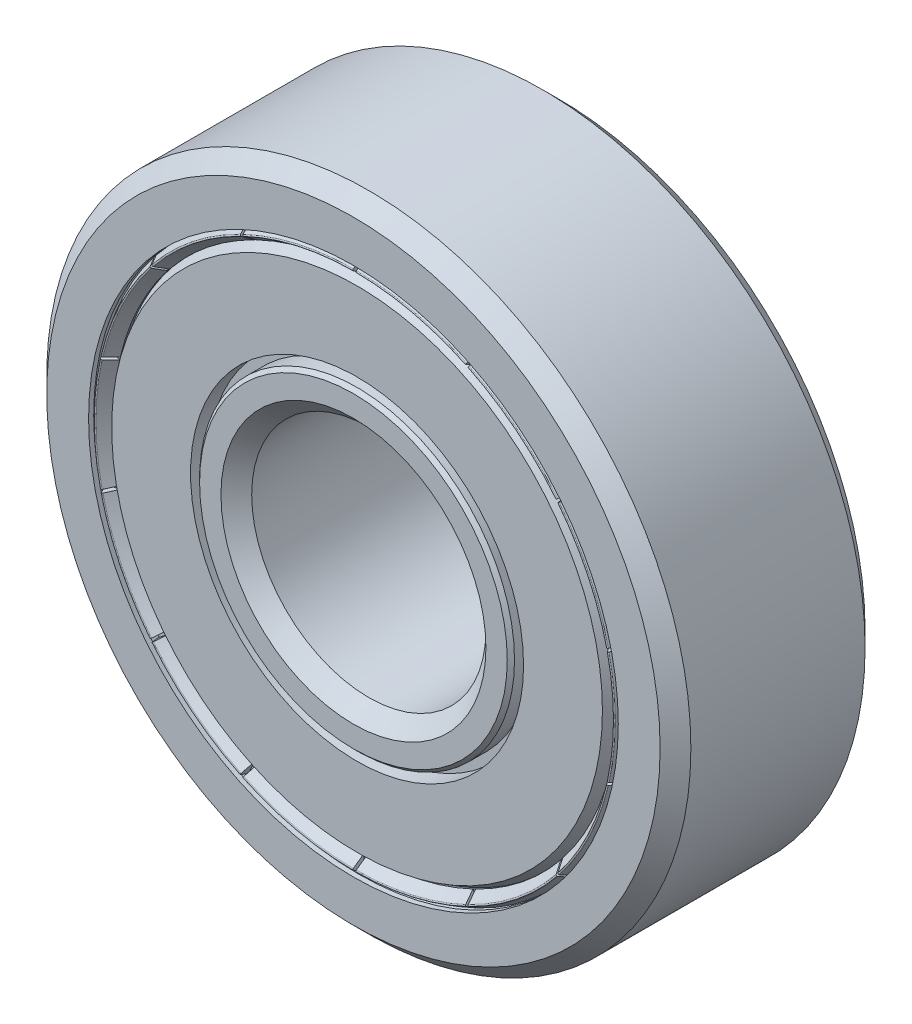
SolidWorks part; units mm, degrees
ref_plane "Front Plane" through (0, 0, 0) normal (0, 0, 1) x (1, 0, 0)
ref_plane "Top Plane" through (0, 0, 0) normal (0, 1, 0) x (1, 0, 0)
ref_plane "Right Plane" through (0, 0, 0) normal (1, 0, 0) x (0, 0, -1)
sketch "Sketch1" plane through (0, 0, 0) normal (0, 0, 1) x (1, 0, 0)
  circle A0 centre (0, 0) radius 4
  circle A1 centre (0, 0) radius 11
  dimension "OD" = 22
  dimension "ID" = 8
sketch "Sketch2" plane through (0, 0, 0) normal (1, 0, 0) x (0, 0, -1)
  line L0 (-3.5, 11) -> (3.5, 11)
  line L1 (-3.5, 4) -> (-3.5, -4) construction
  line L2 (3.5, 11) -> (3.5, -11) construction
  line L3 (-3.5, 0) -> (3.5, 0) construction
  line L6 (0, 11) -> (0, 4) construction
  circle A0 centre (0, 7.5) radius 2.45 construction
  point P8 (0, 11)
  dimension "Approx. Ball Dia." = 4.9
  dimension "Width" = 7
  dimension "For Shaft Diameter" = 8
  dimension "For Housing ID" = 22
sketch "Sketch3" plane through (0, 0, 0) normal (1, 0, 0) x (0, 0, -1)
  line L0 (0, 0) -> (0, 8) construction
  line L1 (-3.5, 4) -> (-3.5, -4) construction
  line L2 (2.975, 11) -> (-2.975, 11)
  line L3 (-2.975, 11) -> (-3.5, 10.475)
  line L4 (-3.5, 10.475) -> (-3.5, 9.046)
  line L5 (-3.5, 9.046) -> (-3.325, 9.046)
  line L6 (-3.325, 9.046) -> (-3.325, 9.498)
  line L7 (-3.325, 9.498) -> (-3.2013, 9.6218)
  line L8 (-3.2013, 9.6218) -> (-1.225, 9.6218)
  line L10 (-3.5, 11) -> (3.5, 11) construction
  line L12 (-3.325, 9.498) -> (-3.325, 9.95) construction
  line L13 (3.2013, 9.6218) -> (1.225, 9.6218)
  line L14 (3.325, 9.498) -> (3.2013, 9.6218)
  line L15 (3.325, 9.046) -> (3.325, 9.498)
  line L16 (3.5, 9.046) -> (3.325, 9.046)
  line L17 (3.5, 10.475) -> (3.5, 9.046)
  line L18 (2.975, 11) -> (3.5, 10.475)
  line L19 (2.975, 4) -> (-2.975, 4)
  line L20 (-2.975, 4) -> (-3.5, 4.525)
  line L21 (-3.5, 4.525) -> (-3.5, 5.2545)
  line L22 (-3.5, 5.2545) -> (-3.3763, 5.3782)
  line L23 (-3.3763, 5.3782) -> (-1.225, 5.3782)
  line L25 (3.3763, 5.3782) -> (1.225, 5.3782)
  line L26 (3.5, 5.2545) -> (3.3763, 5.3782)
  line L27 (3.5, 4.525) -> (3.5, 5.2545)
  line L28 (2.975, 4) -> (3.5, 4.525)
  circle A2 centre (0, 7.5) radius 2.45 construction
  arc A3 (-1.225, 9.6218) -> (1.225, 9.6218) centre (0, 7.5) cw
  arc A4 (-1.225, 5.3782) -> (1.225, 5.3782) centre (0, 7.5) ccw
  point P5 (0, 9.95)
  point P31 (0, 11)
  point P37 (0, 4)
  dimension "D1" = 45
  dimension "D2" = 0.175
  dimension "D3" = 2.45
  dimension "D4" = 0.525
revolve "Revolve1" add sketch "Sketch3" angle 360 about L3
sketch "Sketch4" plane through (0, 0, 0) normal (1, 0, 0) x (0, 0, -1)
  line L0 (0, 9.95) -> (0, 5.05)
  line L1 (0, 11) -> (0, 4) construction
  circle A0 centre (0, 7.5) radius 2.45 construction
  arc A1 (0, 5.05) -> (0, 9.95) centre (0, 7.5) cw
revolve "Revolve2" add sketch "Sketch4" angle 360 about L6
pattern_circular "CirPattern1" count 7 over 360 about axis through (0, 0, 0) along (0, 0, 1) of bodies 106
sketch "Sketch5" plane through (0, 0, 0) normal (1, 0, 0) x (0, 0, -1)
  line L0 (-2.45, 7.5) -> (-2.45, 5.3782) construction
  line L1 (-3.3763, 5.3782) -> (-1.225, 5.3782) construction
  line L3 (-2.45, 5.3782) -> (-2.7588, 5.3782)
  line L4 (-2.7588, 5.3782) -> (-2.7588, 5.687)
  line L5 (-2.7588, 5.687) -> (-3.3763, 5.687)
  line L6 (-3.3763, 5.687) -> (-3.3763, 8.3808)
  line L7 (-3.3763, 8.3808) -> (-2.7588, 8.7373)
  line L8 (-2.7588, 8.7373) -> (-2.45, 8.7373)
  line L9 (-2.45, 8.7373) -> (-2.45, 5.3782)
  line L10 (0, 7.5) -> (0, 11) construction
  line L11 (2.7588, 8.7373) -> (2.45, 8.7373)
  line L12 (3.3763, 8.3808) -> (2.7588, 8.7373)
  line L13 (3.3763, 5.687) -> (3.3763, 8.3808)
  line L14 (2.7588, 5.687) -> (3.3763, 5.687)
  line L15 (2.7588, 5.3782) -> (2.7588, 5.687)
  line L16 (2.45, 5.3782) -> (2.7588, 5.3782)
  line L17 (2.45, 8.7373) -> (2.45, 5.3782)
  line L18 (-3.3763, 8.3808) -> (-3.0675, 8.3808) construction
  line L19 (-3.0675, 8.3808) -> (-2.7588, 8.3808) construction
  line L20 (-2.7588, 8.3808) -> (-2.45, 8.3808) construction
  line L21 (-2.7588, 8.7373) -> (-2.7588, 9.046) construction
  circle A0 centre (0, 7.5) radius 2.45 construction
  dimension "D1" = 30
revolve "Revolve3" add sketch "Sketch5" angle 360 about L3
sketch "Sketch6" plane through (0, 0, 0) normal (1, 0, 0) x (0, 0, -1)
  line L0 (-2.9945, 9.046) -> (-3.1938, 9.046)
  line L1 (-3.1938, 9.046) -> (-3.5, 8.8692)
  line L2 (-3.5, 8.8692) -> (-3.0995, 8.5888)
  line L4 (-3.3763, 8.3808) -> (-2.7588, 8.7373) construction
  line L5 (-2.9945, 8.6012) -> (-2.9945, 9.046)
  line L6 (-3.5, 9.046) -> (-3.325, 9.046) construction
  line L7 (-3.0995, 8.5888) -> (-3.0645, 8.5888)
  line L8 (-3.0645, 8.5888) -> (-2.9945, 8.6012)
  line L9 (-3.5, 10.475) -> (-3.5, -10.475) construction
  line L11 (-3.0645, 8.5888) -> (-3.0295, 8.5888) construction
  line L12 (-3.0295, 8.5888) -> (-2.9945, 8.5888) construction
  point P27 (-3.0941, 9.046)
  dimension "D1" = 30
  dimension "D3" = 10
  dimension "D2" = 35
  dimension "D4" = 0.035
  dimension "D5" = 0.3062
revolve "Revolve4" add sketch "Sketch6" angle 360 about L3
fillet "Fillet1" radius 0.035 1 edges at (8.8692, 0, 3.5)
sketch "Sketch7" plane through (0, 0, 0) normal (0, 0, 1) x (1, 0, 0)
  line L0 (-0.05, 9.046) -> (-0.05, 9.146)
  line L1 (-0.05, 9.046) -> (0.05, 9.046) construction
  line L2 (-0.05, 9.046) -> (-0.05, 8.5888)
  line L3 (-0.05, 8.5888) -> (0.05, 8.5888) construction
  line L4 (0.05, 9.046) -> (0.05, 8.5888)
  line L5 (-0.05, 9.146) -> (0.05, 9.146)
  line L6 (0.05, 9.146) -> (0.05, 9.046)
  line L7 (-0.05, 8.5888) -> (-0.05, 8.4888)
  line L8 (-0.05, 8.4888) -> (0.05, 8.4888)
  line L9 (0.05, 8.4888) -> (0.05, 8.5888)
  dimension "D1" = 0.1
extrude "Cut-Extrude1" cut sketch "Sketch7" along normal through all from vertex at 3.0941 starting at point (0, 9.046, 3.0941)
pattern_circular "CirPattern2" count 14 over 360 about axis through (0, 0, 0) along (0, 0, 1) of "Cut-Extrude1"
mirror "Mirror1" about plane through (0, 0, 0) normal (0, 0, 1) of bodies 120
equation "\"Approx. Ball Dia.@Sketch2\"=( \"OD@Sketch1\" - \"ID@Sketch1\" )  * .5 * .7"
equation "\"D2@Sketch3\"=\"Width@Sketch2\"*.025"
equation "\"D3@Sketch3\"=\"Approx. Ball Dia.@Sketch2\"*.5"
equation "\"D4@Sketch3\"=\"Width@Sketch2\"*.075"
equation "\"Approx No of Balls\"= ( pi * \"OD@Sketch1\" ) * .5 / \"Approx. Ball Dia.@Sketch2\""
equation "\"D1@CirPattern1\"=\"Approx No of Balls\""
equation "\"D4@Sketch6\"=\"D2@Sketch3\"*.2"
equation "\"D1@CirPattern2\"=\"Approx No of Balls\"*2"
equation "\"D5@Sketch6\"=\"D2@Sketch3\"*1.75"
equation "\"D1@Fillet1\"=\"d4@sketch6\""
